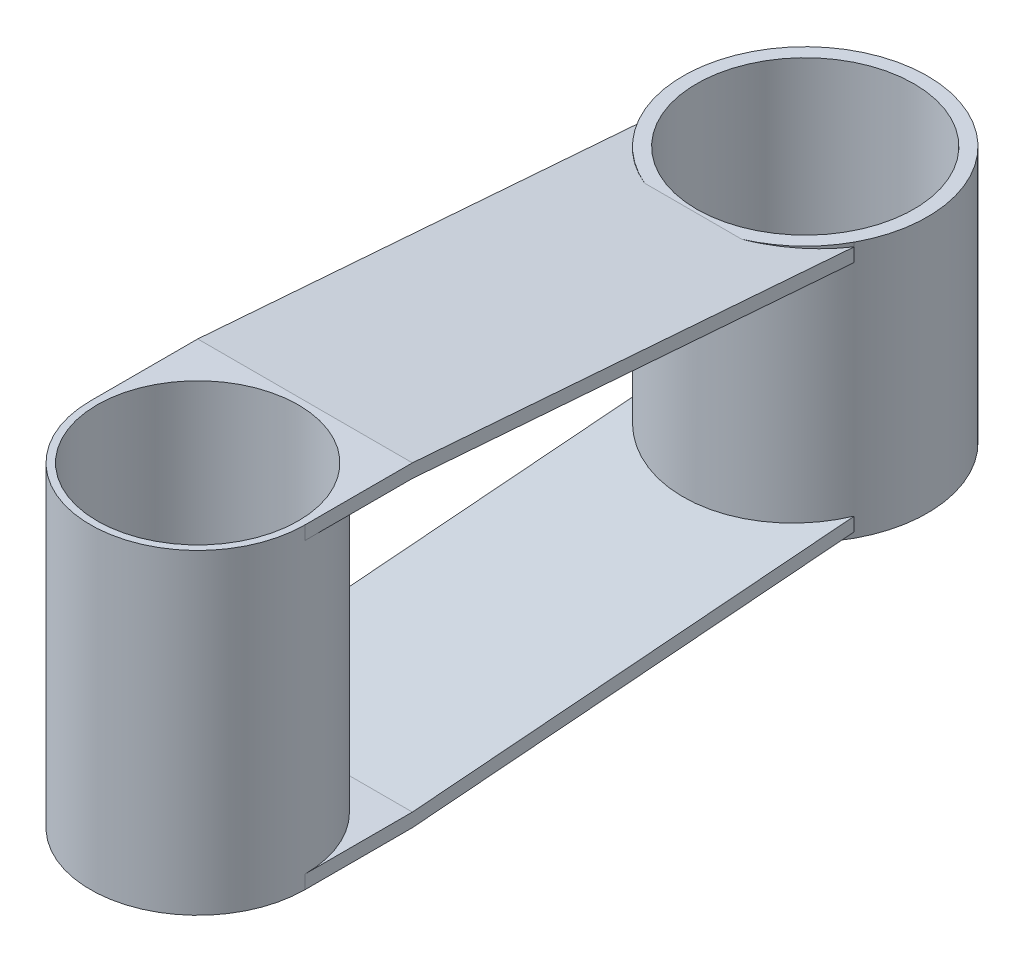
SolidWorks part; units mm, degrees
material "6061-T6 (SS)"
ref_plane "Front Plane" through (0, 0, 0) normal (0, 0, 1) x (1, 0, 0)
ref_plane "Top Plane" through (0, 0, 0) normal (0, 1, 0) x (1, 0, 0)
ref_plane "Right Plane" through (0, 0, 0) normal (1, 0, 0) x (0, 0, -1)
sketch "Sketch1" plane through (0, 0, 0) normal (0, 1, 0) x (1, 0, 0)
  circle A0 centre (0, 0) radius 79.5
  circle A1 centre (0, 0) radius 74.5
  dimension "D1" = 159
  dimension "D2" = 5
extrude "Boss-Extrude1" add sketch "Sketch1" along normal mid plane 234.04
sketch "Sketch2" plane through (0, 0, 0) normal (1, 0, 0) x (0, 0, -1)
  line L0 (450, 111) -> (450, 78.6092) construction
  line L1 (0, 117.02) -> (0, -117.02) construction
  line L2 (79.5, 117.02) -> (-79.5, 117.02) construction
  line L3 (-79.5, -117.02) -> (79.5, -117.02) construction
  line L4 (0, 0) -> (450, 0) construction
  line L5 (79.5, 117.02) -> (450, 88.6385)
  line L6 (79.5, -117.02) -> (450, -87.3724)
  line L7 (450, 88.6385) -> (450, 78.6092)
  line L9 (79.5, -117.02) -> (79.5, 117.02) construction
  line L10 (79.5, -117.02) -> (79.5, -106.988)
  line L11 (450, -77.3404) -> (450, -87.3724)
  line L12 (79.5, 106.9907) -> (450, 78.6092)
  line L14 (79.5, -106.988) -> (450, -77.3404)
  line L17 (79.5, 106.9907) -> (79.5, 117.02)
  dimension "D1" = 450
  dimension "D2" = 10
  dimension "D3" = 10
  dimension "D4" = 4.38
  dimension "D5" = 4.575
extrude "Boss-Extrude2" add sketch "Sketch2" along normal mid plane 159 separate body
sketch "Sketch3" plane through (0, 0, -79.5) normal (0, 0, 1) x (1, 0, 0)
  line L4 (-79.5, -106.988) -> (-79.5, -117.02)
  line L5 (-79.5, -117.02) -> (79.5, -117.02)
  line L6 (79.5, -117.02) -> (79.5, -106.988)
  line L7 (79.5, -106.988) -> (-79.5, -106.988)
  line L8 (-79.5, -106.988) -> (-79.5, -117.02)
  line L9 (-79.5, -117.02) -> (79.5, -117.02)
  line L10 (79.5, -117.02) -> (79.5, -106.988)
  line L11 (79.5, -106.988) -> (-79.5, -106.988)
  line L12 (-79.5, 117.02) -> (-79.5, 106.9907)
  line L13 (-79.5, 106.9907) -> (79.5, 106.9907)
  line L14 (79.5, 106.9907) -> (79.5, 117.02)
  line L15 (79.5, 117.02) -> (-79.5, 117.02)
  line L16 (-79.5, 117.02) -> (-79.5, 106.9907)
  line L17 (-79.5, 106.9907) -> (79.5, 106.9907)
  line L18 (79.5, 106.9907) -> (79.5, 117.02)
  line L19 (79.5, 117.02) -> (-79.5, 117.02)
  dimension "D1" = 0
  dimension "D2" = 0
extrude "Boss-Extrude3" add sketch "Sketch3" along normal up to body separate body
sketch "Sketch4" plane through (0, 0, 0) normal (0, 1, 0) x (1, 0, 0)
  line L0 (0, 0) -> (0, 369.5) construction
  circle A0 centre (0, 450) radius 80.5
  circle A1 centre (0, 450) radius 90.5
  dimension "D3" = 161
  dimension "D1" = 450
  dimension "D2" = 10
extrude "Boss-Extrude4" add sketch "Sketch4" along normal mid plane 190
sketch "Sketch5" plane through (0, 122.3918, -9.3756) normal (0, 0.9971, -0.0764) x (1, 0, 0)
  line L3 (-79.5, 441.9153) -> (-79.5, 429.2291)
  line L4 (79.5, 429.2291) -> (79.5, 441.9153)
  line L5 (79.5, 441.9153) -> (-79.5, 441.9153)
  line L6 (-79.5, 441.9153) -> (-79.5, 429.2291)
  line L7 (79.5, 429.2291) -> (79.5, 441.9153)
  line L8 (79.5, 441.9153) -> (-79.5, 441.9153)
  ellipse E1 centre (0, 441.9153) end of major axis (0, 522.6511) minor radius 80.5 (-79.5, 429.2291) -> (79.5, 429.2291) ccw
  ellipse E2 centre (0, 441.9153) end of major axis (0, 522.6511) minor radius 80.5 (-79.5, 429.2291) -> (79.5, 429.2291) ccw
  dimension "D1" = 0
other "Move Face1" face at (0, 83.6238, -450) face at (0, 83.6238, -450)
sketch "Sketch6" plane through (0, 0, 0) normal (0, 1, 0) x (1, 0, 0)
  circle A0 centre (0, 450) radius 80.5 construction
  circle A1 centre (0, 450) radius 80.5
extrude "Cut-Extrude3" cut sketch "Sketch6" against normal through all both and the other way through all
